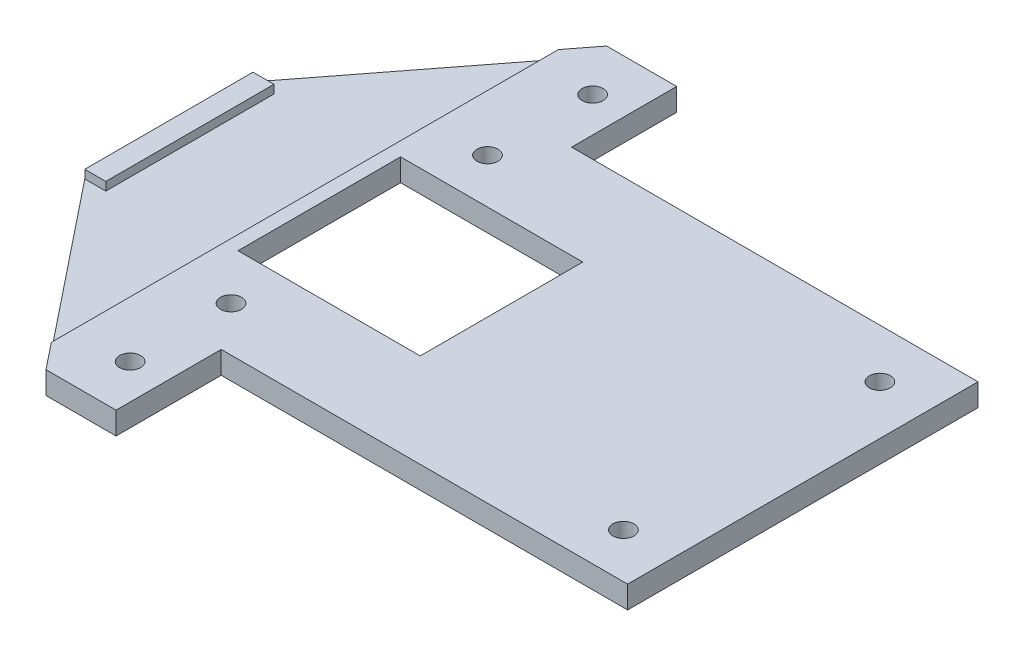
SolidWorks part; units mm, degrees
material "6061 Alloy"
ref_plane "Front Plane" through (0, 0, 0) normal (0, 0, 1) x (1, 0, 0)
ref_plane "Top Plane" through (0, 0, 0) normal (0, 1, 0) x (1, 0, 0)
ref_plane "Right Plane" through (0, 0, 0) normal (1, 0, 0) x (0, 0, -1)
sketch "Sketch2" plane through (0, 0, 0) normal (0, 1, 0) x (1, 0, 0)
  line L0 (0, 5.767) -> (0, -6.233)
  line L1 (0, -6.233) -> (11, -20)
  line L2 (11, -20) -> (45, -20)
  line L3 (45, -20) -> (45, 20)
  line L4 (45, 20) -> (11, 20)
  line L5 (11, 20) -> (0, 5.767)
  point P0 (45, 0)
  dimension "D1" = 12
  dimension "D2" = 11
  dimension "D3" = 40
  dimension "D4" = 45
  dimension "D5" = 13.767
extrude "Boss-Extrude1" add sketch "Sketch2" along normal blind 11.6
sketch "Sketch3" plane through (0, 11.6, 0) normal (0, 1, 0) x (1, 0, 0)
  line L0 (1.5, 7.7079) -> (1.5, -8.1103)
  line L1 (11, 20) -> (0, 5.767) construction
  line L2 (0, -6.233) -> (11, -20) construction
  line L3 (1.5, -8.1103) -> (9.5, -18.1227)
  line L4 (9.5, -18.1227) -> (9.5, 18.0591)
  line L5 (9.5, 18.0591) -> (1.5, 7.7079)
  line L6 (0, 5.767) -> (0, -6.233) construction
  dimension "D1" = 1.5
  dimension "D2" = 8
extrude "Cut-Extrude1" cut sketch "Sketch3" against normal blind 9.85
sketch "Sketch5" plane through (0, 11.6, 0) normal (0, 1, 0) x (1, 0, 0)
  line L0 (9.5, -18.1227) -> (9.5, 18.0591) construction
  line L1 (10.5, 5.8) -> (23.5, 5.8)
  line L2 (10.5, 5.8) -> (10.5, -5.8)
  line L3 (10.5, -5.8) -> (23.5, -5.8)
  line L4 (23.5, 5.8) -> (23.5, -5.8)
  point P4 (10.5, 0)
  dimension "D1" = 11.6
  dimension "D2" = 13
  dimension "D3" = 1
extrude "Cut-Extrude3" cut sketch "Sketch5" against normal through all
sketch "Sketch6" [suppressed] plane through (10.5, 0, 0) normal (1, 0, 0) x (0, 0, -1)
  line L0 (5.8, 0) -> (-5.8, 0) construction
  line L1 (2.5, 6.75) -> (2.5, 11.6)
  line L2 (5.8, 11.6) -> (-5.8, 11.6) construction
  line L3 (2.5, 11.6) -> (-2.5, 11.6)
  line L4 (-2.5, 11.6) -> (-2.5, 6.75)
  arc A0 (-2.5, 6.75) -> (2.5, 6.75) centre (0, 6.75) ccw
  point P5 (0, 0)
  dimension "D2" = 5
  dimension "D1" = 6.75
extrude "Cut-Extrude4" [suppressed] cut sketch "Sketch6" against normal blind 3
sketch "Sketch7" plane through (0, 11.6, 0) normal (0, 1, 0) x (1, 0, 0)
  line L0 (1.5, 7.7079) -> (0, 5.767)
  line L1 (0, 5.767) -> (1.5, 5.767)
  line L2 (1.5, 7.7079) -> (1.5, -8.1103) construction
  line L3 (1.5, 5.767) -> (1.5, 7.7079)
  line L4 (0, -6.233) -> (1.5, -6.233)
  line L5 (1.5, 7.7079) -> (1.5, -8.1103) construction
  line L6 (1.5, -6.233) -> (1.5, -8.1103)
  line L7 (1.5, -8.1103) -> (0, -6.233)
extrude "Cut-Extrude5" cut sketch "Sketch7" against normal up to surface (9.85 mm away) up to face at (5.5, 1.75, 0.1165)
sketch "Sketch8" plane through (0, 0, 0) normal (0, -1, 0) x (1, 0, 0)
  line L0 (23.5, 5.8) -> (23.5, -5.8) construction
  line L1 (10.5, 5.8) -> (23.5, 5.8) construction
  line L2 (23.5, -5.8) -> (10.5, -5.8) construction
  circle A0 centre (16.5, 9.89) radius 1.26
  circle A1 centre (16.5, -9.89) radius 1.26
  dimension "D4" = 2.52
  dimension "D1" = 7
  dimension "D2" = 4.09
  dimension "D3" = 4.09
extrude "Cut-Extrude6" [suppressed] cut sketch "Sketch8" against normal blind 4
sketch "Sketch9" plane through (0, 0, 0) normal (0, -1, 0) x (1, 0, 0)
  line L0 (11, 20) -> (45, 20) construction
  line L1 (16, 20) -> (45, 20)
  line L2 (16, 20) -> (16, 12.5)
  line L3 (16, 12.5) -> (45, 12.5)
  line L4 (45, 20) -> (45, 12.5)
  line L5 (45, 20) -> (45, -20) construction
  line L6 (45, -20) -> (11, -20) construction
  line L7 (16, -20) -> (45, -20)
  line L8 (16, -20) -> (16, -12.5)
  line L9 (16, -12.5) -> (45, -12.5)
  line L10 (45, -20) -> (45, -12.5)
  dimension "D1" = 7.5
  dimension "D2" = 7.5
  dimension "D3" = 5
extrude "Cut-Extrude7" cut sketch "Sketch9" against normal through all
sketch "Sketch10" plane through (0, 11.6, 0) normal (0, 1, 0) x (1, 0, 0)
  line L0 (16, 12.5) -> (16, 20) construction
  line L1 (45, 12.5) -> (16, 12.5) construction
  line L2 (10.5, -5.8) -> (23.5, -5.8) construction
  line L3 (45, -12.5) -> (45, 12.5) construction
  line L4 (11, -20) -> (16, -20) construction
  line L5 (16, 20) -> (11, 20) construction
  circle A0 centre (13.5, 16.5) radius 0.75
  circle A1 centre (13.5, 9) radius 0.75
  circle A2 centre (41.5, 9) radius 0.75
  circle A3 centre (41.5, -9.3) radius 0.75
  circle A4 centre (13.5, -9.3) radius 0.75
  circle A5 centre (13.5, -16.5) radius 0.75
  dimension "D7" = 1.5
  dimension "D1" = 2.5
  dimension "D2" = 3.5
  dimension "D3" = 3.5
  dimension "D4" = 3.5
  dimension "D5" = 3.5
  dimension "D6" = 3.5
extrude "Cut-Extrude8" cut sketch "Sketch10" against normal through all
sketch "Sketch11" plane through (0, 11.6, 0) normal (0, 1, 0) x (1, 0, 0)
  line L0 (9.5, 18.0591) -> (9.5, -18.1227)
  line L1 (0, 5.767) -> (1.5, 5.767)
  line L2 (0, 5.767) -> (0, -6.233)
  line L3 (0, -6.233) -> (1.5, -6.233)
  line L4 (1.5, 5.767) -> (1.5, -6.233)
  line L5 (9.5, 18.0591) -> (0, 5.767) construction
  line L6 (9.5, -18.1227) -> (9.5, 18.0591) construction
  line L7 (9.5, -18.1227) -> (11, -20)
  line L8 (11, -20) -> (16, -20)
  line L9 (16, -20) -> (16, -12.5)
  line L10 (16, -12.5) -> (45, -12.5)
  line L11 (45, -12.5) -> (45, 12.5)
  line L12 (45, 12.5) -> (16, 12.5)
  line L13 (16, 12.5) -> (16, 20)
  line L14 (16, 20) -> (11, 20)
  line L15 (11, 20) -> (9.5, 18.0591)
extrude "Cut-Extrude9" cut sketch "Sketch11" against normal blind 10
sketch "Sketch12" plane through (0, 1.75, 0) normal (0, 1, 0) x (1, 0, 0)
  line L0 (0, 5.767) -> (9.5, 18.0591)
  line L1 (9.5, 18.0591) -> (9.5, -18.1227)
  line L2 (9.5, -18.1227) -> (0, -6.233)
  line L3 (0, -6.233) -> (1.5, -6.233)
  line L4 (1.5, -6.233) -> (1.5, 5.767)
  line L5 (1.5, 5.767) -> (0, 5.767)
extrude "Cut-Extrude10" cut sketch "Sketch12" against normal blind 0.75
